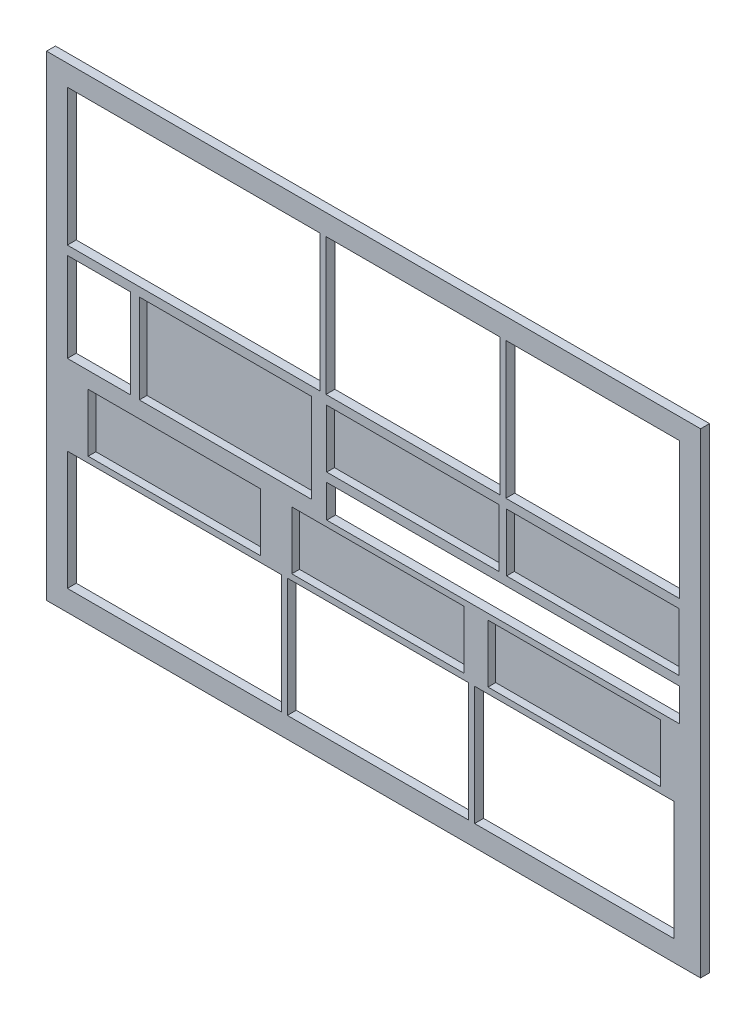
SolidWorks part; units mm, degrees
ref_plane "Front Plane" through (0, 0, 0) normal (0, 0, 1) x (1, 0, 0)
ref_plane "Top Plane" through (0, 0, 0) normal (0, 1, 0) x (1, 0, 0)
ref_plane "Right Plane" through (0, 0, 0) normal (1, 0, 0) x (0, 0, -1)
sketch "草图1" plane through (0, 0, 0) normal (0, 0, 1) x (1, 0, 0)
  line L0 (-110, 0) -> (110, 0) construction
  line L1 (-110, 80) -> (-110, -80)
  line L2 (-110, 80) -> (110, 80)
  line L3 (110, 80) -> (110, -80)
  line L4 (110, -80) -> (-110, -80)
  point P4 (0, 0)
  point P8 (-110, 0)
  point P15 (0, 73)
  dimension "D1" = 160
  dimension "D2" = 220
extrude "凸台-拉伸1" add sketch "草图1" along normal blind 3
sketch "草图2" plane through (0, 0, 3) normal (0, 0, 1) x (1, 0, 0)
  line L0 (0, 80) -> (0, 73) construction
  line L1 (110, 80) -> (-110, 80) construction
  line L2 (-103, 73) -> (103, 73)
  line L3 (-103, 80) -> (-103, 27) construction
  line L4 (-103, 73) -> (-103, 27)
  line L5 (-103, 27) -> (103, 27)
  line L6 (103, 27) -> (103, 73)
  line L7 (-110, 73) -> (-18, 73) construction
  line L8 (-110, 80) -> (-110, -80) construction
  line L9 (-18, 73) -> (-18, 27)
  line L10 (-18, 50) -> (-16, 50) construction
  line L11 (-16, 27) -> (-16, 73)
  line L12 (110, 73) -> (44.5, 73) construction
  line L13 (110, -80) -> (110, 80) construction
  line L14 (44.5, 73) -> (42.5, 73) construction
  line L15 (42.5, 73) -> (42.5, 27)
  line L16 (44.5, 73) -> (44.5, 27)
  point P8 (0, 73)
  point P21 (-16, 50)
  dimension "D1" = 92
  dimension "D2" = 58.5
  dimension "D3" = 58.5
  dimension "D4" = 7
extrude "切除-拉伸1" cut sketch "草图2" against normal through all contours L9 L2 L4 L5 | L15 L2 L11 L5 | L2 L16 L5 L6
sketch "草图3" plane through (0, 0, 3) normal (0, 0, 1) x (1, 0, 0)
  line L0 (-103, 27) -> (-103, 24) construction
  line L1 (-103, 24) -> (-103, -6)
  line L2 (-103, 24) -> (-81.8, 24)
  line L3 (-81.8, 24) -> (-81.8, -6)
  line L4 (-81.8, -6) -> (-103, -6)
  dimension "D1" = 3
  dimension "D2" = 30
extrude "切除-拉伸2" cut sketch "草图3" against normal up to next
sketch "草图4" plane through (0, 0, 3) normal (0, 0, 1) x (1, 0, 0)
  line L0 (-81.8, 9) -> (-78.8, 9) construction
  line L1 (-81.8, -6) -> (-81.8, 24) construction
  line L2 (-78.8, 24) -> (-78.8, -6)
  line L3 (-78.8, -6) -> (-20.8, -6)
  line L4 (-20.8, -6) -> (-20.8, 24)
  line L5 (-20.8, 24) -> (-78.8, 24)
  line L6 (13.25, 27) -> (13.25, 24) construction
  line L7 (-15.75, 24) -> (-15.75, 4.5)
  line L8 (73.75, 27) -> (73.75, 24) construction
  line L9 (44.5, 27) -> (103, 27) construction
  line L10 (-15.75, 24) -> (42.25, 24)
  line L11 (42.25, 24) -> (42.25, 4.5)
  line L12 (42.25, 4.5) -> (-15.75, 4.5)
  line L17 (44.75, 24) -> (102.75, 24)
  line L18 (-16, 27) -> (42.5, 27) construction
  line L19 (44.75, 24) -> (44.75, 4.5)
  line L20 (44.75, 4.5) -> (102.75, 4.5)
  line L21 (102.75, 4.5) -> (102.75, 24)
  point P7 (-78.8, 9)
  point P19 (72.9389, 32.6178)
  point P22 (13.25, 24)
  point P25 (73.75, 24)
  dimension "D1" = 58
  dimension "D2" = 0
  dimension "D3" = 19.5
  dimension "D4" = 3
extrude "切除-拉伸3" cut sketch "草图4" against normal offset from surface (2.6 mm away) 0.4 up to face at (-92.4, 9, 0)
sketch "草图5" plane through (0, 0, 3) normal (0, 0, 1) x (1, 0, 0)
sketch "草图6" plane through (0, 0, 3) normal (0, 0, 1) x (1, 0, 0)
  line L0 (-15.75, 4.5) -> (-15.75, 1.5) construction
  line L1 (-15.75, 1.5) -> (103, 1.5)
  line L2 (103, 1.5) -> (103, -9.5)
  line L3 (103, -9.5) -> (-15.75, -9.5)
  line L4 (-15.75, -9.5) -> (-15.75, 1.5)
extrude "切除-拉伸4" cut sketch "草图6" against normal through all
sketch "草图7" plane through (0, 0, 3) normal (0, 0, 1) x (1, 0, 0)
  line L0 (-103, -80) -> (-103, -73) construction
  line L1 (-110, -80) -> (110, -80) construction
  line L2 (-103, -73) -> (-103, -33)
  line L3 (-103, -33) -> (-31, -33)
  line L4 (-31, -33) -> (-31, -73)
  line L5 (-31, -73) -> (-103, -73)
  line L6 (-31, -53) -> (-29, -53) construction
  line L7 (-29, -73) -> (-29, -33)
  line L8 (-29, -33) -> (32, -33)
  line L9 (32, -33) -> (32, -73)
  line L10 (32, -73) -> (-29, -73)
  line L11 (32, -53) -> (34, -53) construction
  line L12 (34, -73) -> (34, -33)
  line L13 (34, -33) -> (101, -33)
  line L14 (101, -33) -> (101, -73)
  line L15 (101, -73) -> (34, -73)
  point P12 (-29, -53)
  point P19 (34, -53)
  dimension "D1" = 72
extrude "切除-拉伸5" cut sketch "草图7" against normal up to next
sketch "草图8" plane through (0, 0, 3) normal (0, 0, 1) x (1, 0, 0)
  line L0 (-67, -33) -> (-67, -31) construction
  line L1 (-31, -33) -> (-103, -33) construction
  line L2 (-96, -31) -> (-38, -31)
  line L3 (-96, -31) -> (-96, -11.5)
  line L4 (-96, -11.5) -> (-38, -11.5)
  line L5 (-38, -11.5) -> (-38, -31)
  line L6 (1.5, -33) -> (1.5, -31) construction
  line L7 (32, -33) -> (-29, -33) construction
  line L8 (-27.5, -31) -> (30.5, -31)
  line L9 (30.5, -31) -> (30.5, -11.5)
  line L10 (30.5, -11.5) -> (-27.5, -11.5)
  line L11 (-27.5, -11.5) -> (-27.5, -31)
  line L13 (67.5, -33) -> (67.5, -31) construction
  line L14 (101, -33) -> (34, -33) construction
  line L15 (38.5, -31) -> (96.5, -31)
  line L16 (38.5, -31) -> (38.5, -11.5)
  line L17 (38.5, -11.5) -> (96.5, -11.5)
  line L18 (96.5, -11.5) -> (96.5, -31)
  point P7 (-67, -31)
  point P16 (1.5, -31)
  point P25 (67.5, -31)
extrude "切除-拉伸6" cut sketch "草图8" against normal offset from surface (2.6 mm away) 0.4 up to face at (-67, -53, 0)
